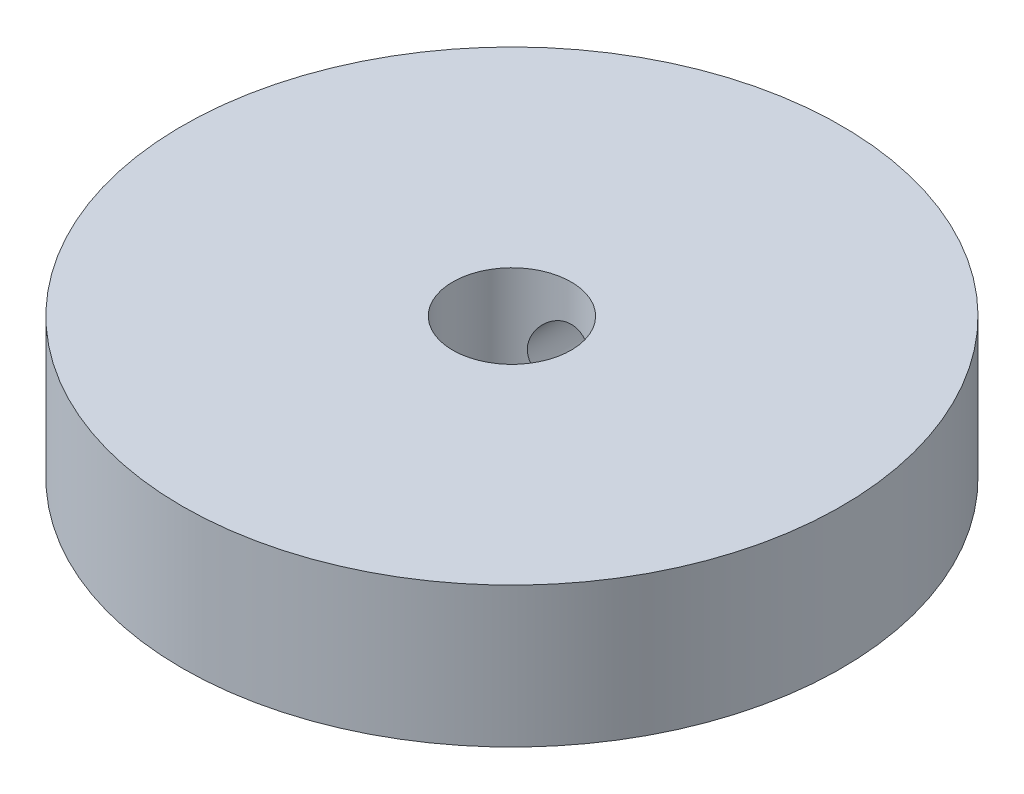
SolidWorks part; units mm, degrees
ref_plane "Front Plane" through (0, 0, 0) normal (0, 0, 1) x (1, 0, 0)
ref_plane "Top Plane" through (0, 0, 0) normal (0, 1, 0) x (1, 0, 0)
ref_plane "Right Plane" through (0, 0, 0) normal (1, 0, 0) x (0, 0, -1)
sketch "Sketch1" plane through (0, 0, 0) normal (0, 1, 0) x (1, 0, 0)
  circle A0 centre (0, 0) radius 11.7475
  circle A1 centre (0, 0) radius 2.11
  dimension "D1" = 23.495
  dimension "D2" = 4.22
extrude "Boss-Extrude1" add sketch "Sketch1" along normal mid plane 5
sketch "Sketch2" plane through (0, 0, 0) normal (0, 0, 1) x (1, 0, 0)
  circle A0 centre (0, 0) radius 1.1929
extrude "Cut-Extrude1" cut sketch "Sketch2" against normal through all
